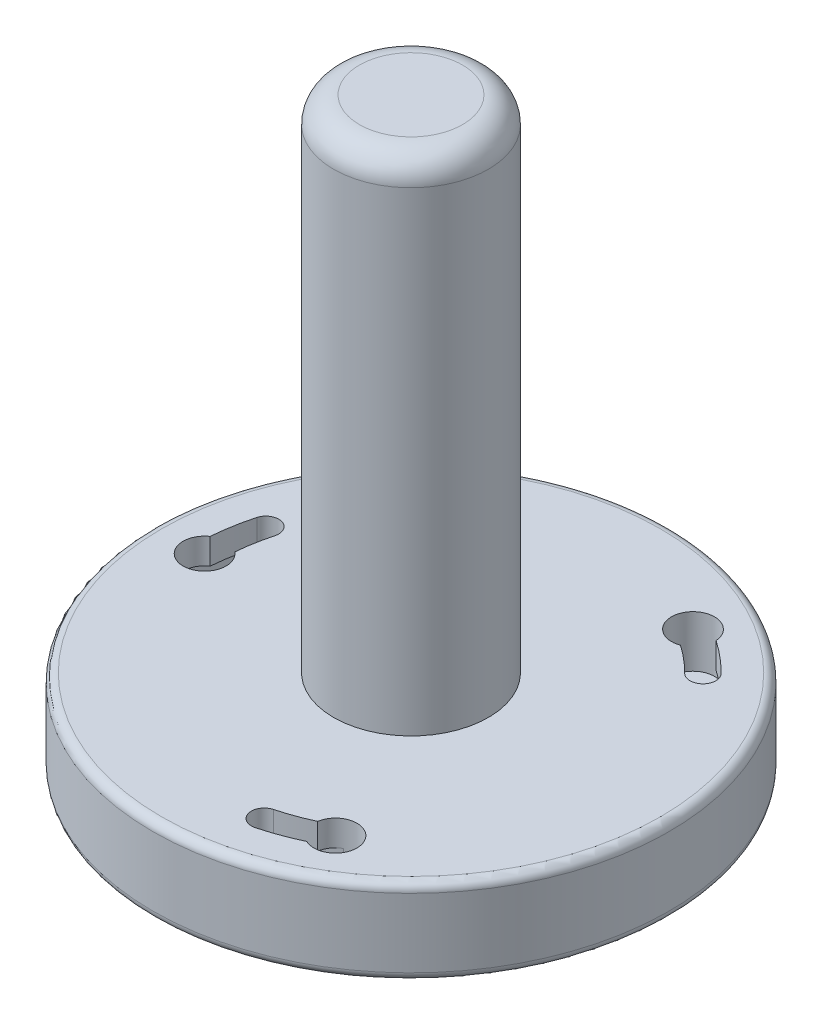
SolidWorks part; units mm, degrees
material "Nylon 101"
ref_plane "Front Plane" through (0, 0, 0) normal (0, 0, 1) x (1, 0, 0)
ref_plane "Top Plane" through (0, 0, 0) normal (0, 1, 0) x (1, 0, 0)
ref_plane "Right Plane" through (0, 0, 0) normal (1, 0, 0) x (0, 0, -1)
sketch "Sketch1" plane through (0, 0, 0) normal (0, 1, 0) x (1, 0, 0)
  circle A0 centre (0, 0) radius 38.1
extrude "Boss-Extrude1" add sketch "Sketch1" along normal blind 12.7
sketch "Sketch2" plane through (0, 12.7, 0) normal (0, 1, 0) x (1, 0, 0)
  circle A0 centre (0, 0) radius 11.43
  dimension "D1" = 22.86
extrude "Boss-Extrude2" add sketch "Sketch2" along normal blind 73.914
sketch "Sketch3" plane through (0, 0, 0) normal (0, -1, 0) x (-1, 0, 0)
  line L0 (0, 0) -> (0, -31.75)
  line L1 (0, 0) -> (-27.4963, 15.875)
  line L2 (0, 0) -> (27.4963, 15.875)
  line L3 (0, 0) -> (3.2996, 1.905)
  line L4 (0, 0) -> (-3.2996, 1.905)
  line L5 (0, 0) -> (0, -3.81)
  line L6 (-3.2996, 1.905) -> (3.2996, 1.905)
  line L7 (-3.2996, 1.905) -> (-3.2996, -31.3982)
  line L8 (3.2996, 1.905) -> (3.2996, -31.3982)
  line L9 (-3.2996, -31.3982) -> (3.2996, -31.3982)
  line L10 (0, -3.81) -> (3.2996, 1.905)
  line L11 (0, -3.81) -> (-29.105, 12.9938)
  line L12 (3.2996, 1.905) -> (-22.5059, 16.8038)
  line L13 (-29.105, 12.9938) -> (-25.8054, 18.7088)
  line L14 (0, -3.81) -> (-3.2996, 1.905)
  line L15 (0, -3.81) -> (28.9716, 12.9168)
  line L16 (-3.2996, 1.905) -> (8.9711, 8.9894)
  line L17 (28.9716, 12.9168) -> (25.672, 18.6318)
  line L18 (25.672, 18.6318) -> (23.2759, 21.5939)
  line L20 (-25.8054, 18.7088) -> (-23.2759, 21.5939)
  line L21 (-25.8054, 18.7088) -> (-25.6976, 18.6465)
  line L22 (-25.6976, 18.6465) -> (-25.8054, 18.7088)
  line L24 (-8.9711, 8.9894) -> (-12.2706, 10.8944)
  line L25 (-9.8562, 9.5005) -> (-13.1557, 11.4055)
  line L26 (-8.9711, 8.9894) -> (-5.901, 11.2458)
  line L27 (5.901, 11.2458) -> (5.8917, 11.2507)
  line L28 (12.2706, 10.8944) -> (22.3725, 16.7268)
  arc A0 (5.9327, 11.2291) -> (8.9711, 8.9894) centre (0, 0) ccw
  circle A1 centre (0, 0) radius 31.75
  arc A2 (22.3725, 16.7268) -> (23.2759, 21.5939) centre (19.9763, 19.6889) ccw
  arc A3 (-23.2759, 21.5939) -> (-22.5059, 16.8038) centre (-19.9902, 19.6651) ccw
  arc A4 (5.901, 11.2458) -> (12.2706, 10.8944) centre (9.467, 17.9799) ccw
  circle A5 centre (-9.467, 17.9799) radius 7.62
  dimension "D1" = 25.4
  dimension "D10" = 7.62
  dimension "D12" = 7.62
  dimension "D18" = 15.24
  dimension "D19" = 3.81
  dimension "D2" = 31.75
  dimension "D3" = 120
  dimension "D4" = 120
  dimension "D5" = 3.81
  dimension "D6" = 3.81
  dimension "D7" = 3.81
  dimension "D8" = 3.81
  dimension "D9" = 3.81
  dimension "D11" = 3.81
  dimension "D13" = 29.6435
  dimension "D14" = 3.81
  dimension "D15" = 3.81
  dimension "D16" = 29.7975
  dimension "D17" = 3.81
fillet "Fillet1" radius 1.27 1 edges at (0, 12.7, 38.1)
fillet "Fillet2" radius 1.27 1 edges at (0, 0, 38.1)
fillet "Fillet3" radius 3.81 1 edges at (0, 86.614, 11.43)
ref_plane "Plane1" through (0, 5.08, 0) normal (0, -1, 0) x (-1, 0, 0)
sketch "Sketch4" plane through (0, 12.7, 0) normal (0, -1, 0) x (-1, 0, 0)
  line L0 (30.48, 0) -> (0, 0) construction
  line L1 (0, 0) -> (-15.24, -26.3965) construction
  line L2 (0, 0) -> (-15.24, 26.3965) construction
  arc A0 (-12.1067, -25.8836) -> (-13.874, -29.2626) centre (-15.24, -26.3965) ccw
  arc A1 (28.4692, 2.4571) -> (32.2792, 2.616) centre (30.48, 0) ccw
  arc A2 (-13.874, -29.2626) -> (-8.2865, -31.3069) centre (0, 0) ccw
  arc A3 (-12.1067, -25.8836) -> (-7.3117, -27.6237) centre (0, 0) ccw
  arc A4 (-8.2865, -31.3069) -> (-7.3117, -27.6237) centre (-7.7991, -29.4653) ccw
  arc A5 (-16.3625, 23.4265) -> (-18.4051, 26.6466) centre (-15.24, 26.3965) ccw
  arc A6 (31.2558, 8.4771) -> (27.5787, 7.4798) centre (29.4173, 7.9784) ccw
  arc A7 (32.2792, 2.616) -> (31.2558, 8.4771) centre (0, 0) ccw
  arc A8 (28.4692, 2.4571) -> (27.5787, 7.4798) centre (0, 0) ccw
  arc A9 (-18.4051, 26.6466) -> (-22.9693, 22.8298) centre (0, 0) ccw
  arc A10 (-16.3625, 23.4265) -> (-20.267, 20.1439) centre (0, 0) ccw
  arc A11 (-22.9693, 22.8298) -> (-20.267, 20.1439) centre (-21.6182, 21.4869) ccw
  point P25 (0, 0)
  dimension "D1" = 3.175
  dimension "D2" = 6.35
  dimension "D3" = 120
  dimension "D5" = 3.81
  dimension "D6" = 1.905
  dimension "D7" = 32.385
  dimension "D4" = 120
  dimension "D8" = 3
extrude "Cut-Extrude2" cut sketch "Sketch4" along normal blind 3.81
sketch "Sketch5" plane through (0, 8.89, 0) normal (0, 1, 0) x (1, 0, 0)
  arc A0 (16.8275, -29.1461) -> (13.6525, -23.6468) centre (15.24, -26.3965) ccw
  arc A1 (6.9867, -26.396) -> (8.6115, -32.5346) centre (7.7991, -29.4653) ccw
  arc A2 (8.6115, -32.5346) -> (16.8275, -29.1461) centre (0, 0) ccw
  arc A3 (6.9867, -26.396) -> (13.6525, -23.6468) centre (0, 0) ccw
  arc A4 (-32.4816, 8.8095) -> (-33.655, 0) centre (0, 0) ccw
  arc A5 (-33.655, 0) -> (-27.305, 0) centre (-30.48, 0) ccw
  arc A6 (-26.353, 7.1474) -> (-27.305, 0) centre (0, 0) ccw
  arc A7 (-26.353, 7.1474) -> (-32.4816, 8.8095) centre (-29.4173, 7.9784) ccw
  arc A8 (23.8701, 23.7251) -> (16.8275, 29.1461) centre (0, 0) ccw
  arc A9 (16.8275, 29.1461) -> (13.6525, 23.6468) centre (15.24, 26.3965) ccw
  arc A10 (19.3663, 19.2487) -> (13.6525, 23.6468) centre (0, 0) ccw
  arc A11 (19.3663, 19.2487) -> (23.8701, 23.7251) centre (21.6182, 21.4869) ccw
  point P24 (0, 0)
  dimension "D1" = 3
extrude "Cut-Extrude3" cut sketch "Sketch5" against normal blind 3.81
